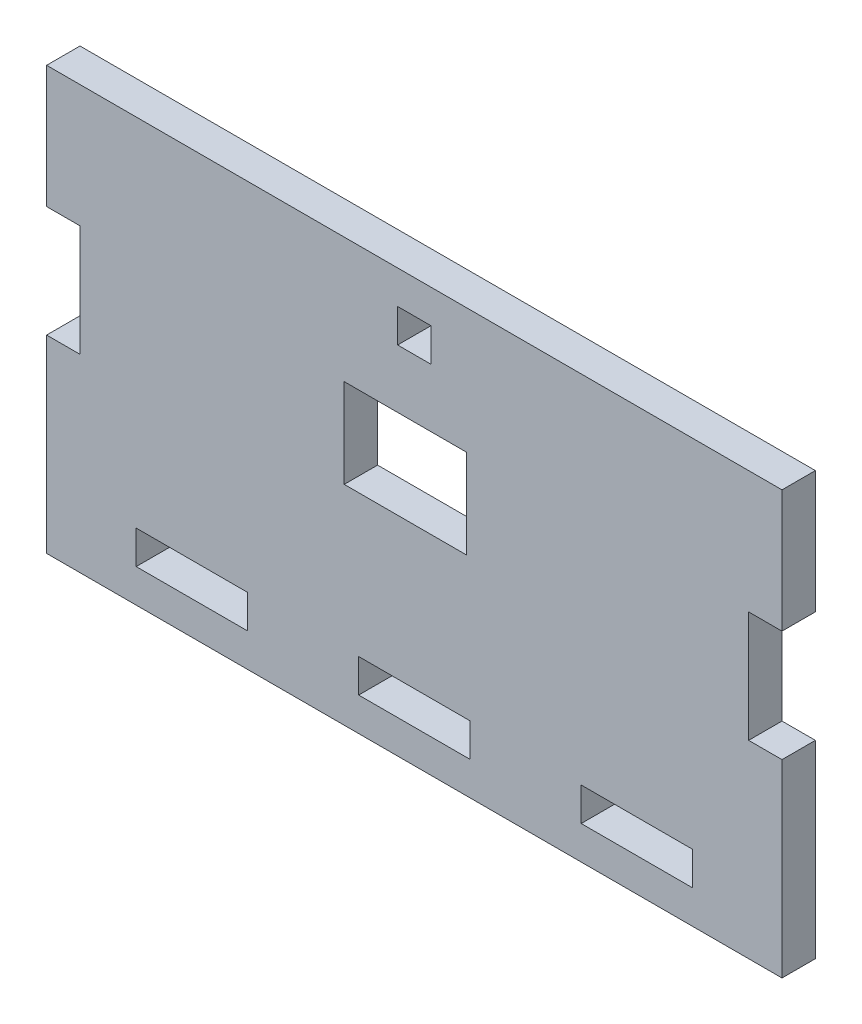
SolidWorks part; units mm, degrees
ref_plane "Front Plane" through (0, 0, 0) normal (0, 0, 1) x (1, 0, 0)
ref_plane "Top Plane" through (0, 0, 0) normal (0, 1, 0) x (1, 0, 0)
ref_plane "Right Plane" through (0, 0, 0) normal (1, 0, 0) x (0, 0, -1)
sketch "Sketch1" plane through (0, 0, 0) normal (0, 0, 1) x (1, 0, 0)
  line L0 (-28.0561, 24.8093) -> (-28.0561, -22.86) construction
  line L1 (-61.1061, 24.8093) -> (4.9939, 24.8093)
  line L2 (-61.1061, 24.8093) -> (-61.1061, -13.1907)
  line L3 (-61.1061, -13.1907) -> (4.9939, -13.1907)
  line L4 (4.9939, 24.8093) -> (4.9939, -13.1907)
  line L5 (4.9939, 13.8093) -> (1.9939, 13.8093)
  line L6 (1.9939, 13.8093) -> (1.9939, 3.8093)
  line L7 (1.9939, 3.8093) -> (4.9939, 3.8093)
  line L8 (-33.0561, -10.1907) -> (-23.0561, -10.1907)
  line L9 (-3.0561, -7.1907) -> (-13.0561, -7.1907)
  line L10 (-3.0561, -7.1907) -> (-3.0561, -10.1907)
  line L11 (-3.0561, -10.1907) -> (-13.0561, -10.1907)
  line L12 (-13.0561, -7.1907) -> (-13.0561, -10.1907)
  line L13 (-34.3561, 13.5593) -> (-23.3561, 13.5593)
  line L14 (-34.3561, 13.5593) -> (-34.3561, 5.5593)
  line L15 (-34.3561, 5.5593) -> (-23.3561, 5.5593)
  line L16 (-23.3561, 13.5593) -> (-23.3561, 5.5593)
  line L17 (-23.0561, -10.1907) -> (-23.0561, -7.1907)
  line L18 (-23.0561, -7.1907) -> (-33.0561, -7.1907)
  line L19 (-33.0561, -10.1907) -> (-33.0561, -7.1907)
  line L20 (-43.0561, -7.1907) -> (-43.0561, -10.1907)
  line L21 (-53.0561, -10.1907) -> (-43.0561, -10.1907)
  line L22 (-53.0561, -7.1907) -> (-53.0561, -10.1907)
  line L23 (-53.0561, -7.1907) -> (-43.0561, -7.1907)
  line L24 (-58.1061, 3.8093) -> (-61.1061, 3.8093)
  line L25 (-58.1061, 13.8093) -> (-58.1061, 3.8093)
  line L26 (-61.1061, 13.8093) -> (-58.1061, 13.8093)
  line L27 (-29.5561, 21.8093) -> (-26.5561, 21.8093)
  line L28 (-26.5561, 21.8093) -> (-26.5561, 18.8093)
  line L29 (-26.5561, 18.8093) -> (-29.5561, 18.8093)
  line L30 (-29.5561, 21.8093) -> (-29.5561, 18.8093)
  point P22 (-28.0561, -10.1907)
  point P24 (-28.0561, -7.1907)
  point P32 (-28.8561, 5.5593)
  point P37 (-28.0561, 18.8093)
  point P38 (-28.0561, 21.8093)
  dimension "D1" = 66.1
  dimension "D2" = 38
  dimension "D3" = 3
  dimension "D4" = 10
  dimension "D5" = 11
  dimension "D6" = 17
  dimension "D7" = 10
  dimension "D8" = 3
  dimension "D9" = 8.05
  dimension "D10" = 3
  dimension "D11" = 11
  dimension "D12" = 8
  dimension "D13" = 12.75
  dimension "D14" = 23.75
  dimension "D15" = 5
  dimension "D16" = 3
  dimension "D17" = 3
  dimension "D18" = 3
  dimension "D19" = 1.5
  dimension "D20" = 3
extrude "Boss-Extrude1" add sketch "Sketch1" along normal blind 3 contours L0 L1 L2 L26 L25 L24 L3 L8 L19 L18 L22 L23 L20 L21 | L1 L0 L18 L17 L8 L3 L4 L7 L6 L5 L13 L16 L15 L14 L12 L9 L10 L11
